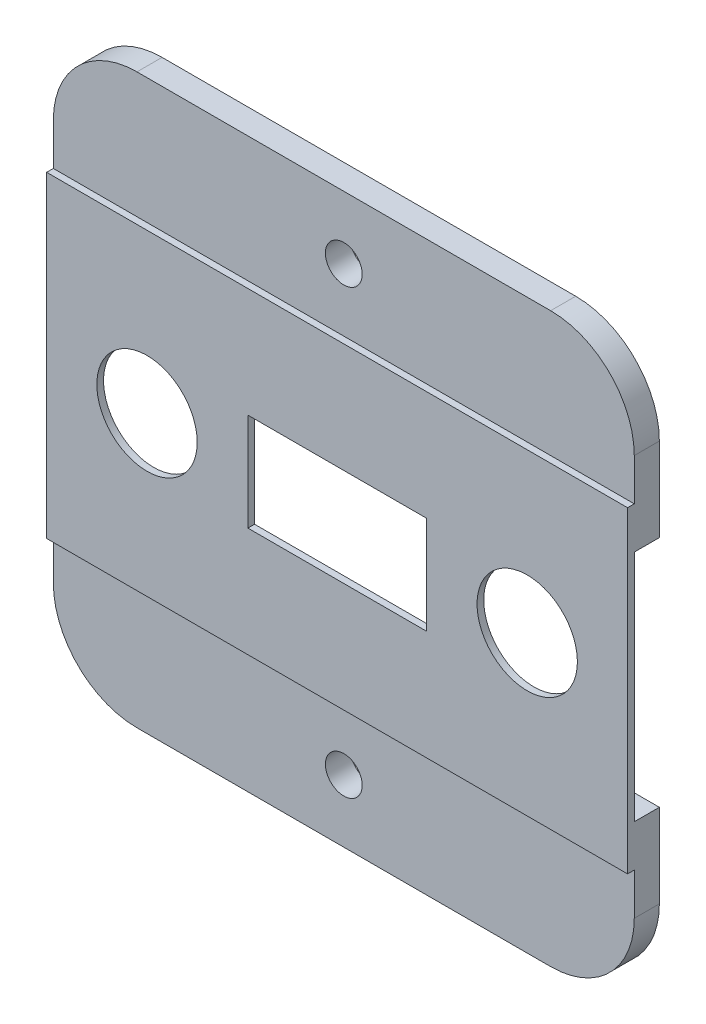
SolidWorks part; units mm, degrees
ref_plane "Front Plane" through (0, 0, 0) normal (0, 0, 1) x (1, 0, 0)
ref_plane "Top Plane" through (0, 0, 0) normal (0, 1, 0) x (1, 0, 0)
ref_plane "Right Plane" through (0, 0, 0) normal (1, 0, 0) x (0, 0, -1)
sketch "Sketch1" plane through (0, 0, 0) normal (0, 0, 1) x (1, 0, 0)
  line L1 (-26.7562, -18.6229) -> (-26.7562, -12.2729)
  line L2 (-20.4062, -5.9229) -> (11.0009, -5.9229)
  line L51 (-14.1451, -18.6229) -> (15.7083, -18.6229)
  line L52 (-26.7562, -18.6229) -> (17.3509, -18.6229) construction
  line L54 (-14.1451, -36.3521) -> (15.7083, -36.3521)
  line L55 (-26.7562, -36.3521) -> (17.3509, -36.3521) construction
  line L56 (-26.7562, -36.3521) -> (17.3509, -36.3521)
  line L57 (-26.7562, -36.3521) -> (-26.7562, -42.7021)
  line L58 (-20.4062, -49.0521) -> (11.0009, -49.0521)
  line L59 (17.3509, -36.3521) -> (17.3509, -42.7021)
  line L60 (17.3509, -18.6229) -> (-26.7562, -18.6229)
  line L61 (17.3509, -18.6229) -> (17.3509, -12.2729)
  circle A0 centre (-19.1362, -27.4875) radius 1.319 construction
  circle A1 centre (9.7309, -27.4875) radius 1.319 construction
  circle A2 centre (-19.1362, -27.4875) radius 1.319 construction
  circle A3 centre (9.7309, -27.4875) radius 1.319 construction
  arc A8 (-20.4062, -49.0521) -> (-26.7562, -42.7021) centre (-20.4062, -42.7021) cw
  arc A9 (11.0009, -49.0521) -> (17.3509, -42.7021) centre (11.0009, -42.7021) ccw
  arc A10 (11.0009, -5.9229) -> (17.3509, -12.2729) centre (11.0009, -12.2729) cw
  arc A11 (-26.7562, -12.2729) -> (-20.4062, -5.9229) centre (-20.4062, -12.2729) cw
  point P0 (17.3509, -8.3311)
  point P3 (-26.7562, -49.0521)
  point P21 (-26.7562, -49.0521)
  dimension "D6" = 7.62
  dimension "D4" = 6.35
  dimension "D3" = 12.7
  dimension "D5" = 7.62
  dimension "D1" = 0.508
  dimension "D2" = 0.508
extrude "Boss-Extrude1" add sketch "Sketch1" along normal offset from surface (1.905 mm away) 0.381 contours L60 L1 A11 L2 A10 L61 | L58 A9 L59 L56 L57 A8
sketch "Sketch2" plane through (0, 0, 1.905) normal (0, 0, 1) x (1, 0, 0)
  line L0 (-10.7161, -30.2624) -> (-10.7161, -30.4402) construction
  line L1 (-26.7562, -39.5271) -> (17.3509, -39.5271)
  line L7 (17.3509, -15.4479) -> (-26.7562, -15.4479)
  line L9 (-10.7161, -30.2624) -> (-10.7161, -24.7125) construction
  line L10 (-10.7161, -24.5347) -> (-10.7161, -24.7125) construction
  line L11 (1.3108, -24.5347) -> (-10.7161, -24.5347) construction
  line L12 (1.3108, -30.4402) -> (1.3108, -24.5347) construction
  line L13 (-10.7161, -30.4402) -> (1.3108, -30.4402) construction
  line L14 (-10.7161, -30.2624) -> (-10.7161, -30.4402) construction
  line L15 (-10.7161, -30.2624) -> (-10.7161, -24.7125) construction
  line L16 (-10.7161, -24.5347) -> (-10.7161, -24.7125) construction
  line L17 (1.3108, -24.5347) -> (-10.7161, -24.5347) construction
  line L18 (1.3108, -30.4402) -> (1.3108, -24.5347) construction
  line L19 (-10.7161, -30.4402) -> (1.3108, -30.4402) construction
  line L20 (-11.4781, -23.7727) -> (-11.4781, -24.7125)
  line L21 (-11.4781, -30.2624) -> (-11.4781, -24.7125)
  line L26 (-11.4781, -30.2624) -> (-11.4781, -31.2022)
  line L27 (-11.4781, -31.2022) -> (2.0728, -31.2022)
  line L30 (2.0728, -31.2022) -> (2.0728, -23.7727)
  line L31 (2.0728, -23.7727) -> (-11.4781, -23.7727)
  line L32 (17.3509, -18.6229) -> (-26.7562, -18.6229) construction
  line L33 (-26.7562, -15.4479) -> (-26.7562, -39.5271)
  line L35 (17.3509, -39.5271) -> (17.3509, -15.4479)
  circle A0 centre (-19.1362, -27.4875) radius 1.397 construction
  circle A1 centre (9.7309, -27.4875) radius 1.397 construction
  circle A2 centre (-19.1362, -27.4875) radius 1.397 construction
  circle A3 centre (9.7309, -27.4875) radius 1.397 construction
  circle A4 centre (9.7309, -27.4875) radius 3.81
  circle A5 centre (-19.1362, -27.4875) radius 3.81
  arc A10 (4.7906, -23.6775) -> (4.7906, -31.2975) centre (4.7906, -27.4875) ccw construction
  point P0 (-25.0322, -39.5329)
  point P37 (-10.7161, -27.4875)
  point P45 (-26.7562, -27.4875)
  dimension "D3" = 0.762
  dimension "D5" = 7.62
  dimension "D1" = 7.62
  dimension "D4" = 3.175
extrude "Boss-Extrude2" add sketch "Sketch2" along normal blind 0.508
sketch "Sketch3" plane through (0, 0, 1.905) normal (0, 0, 1) x (1, 0, 0)
  line L0 (17.3509, -15.4479) -> (-26.7562, -15.4479) construction
  line L1 (-26.7562, -39.5271) -> (17.3509, -39.5271) construction
  line L2 (-20.4062, -49.0521) -> (11.0009, -49.0521) construction
  line L3 (-20.4062, -5.9229) -> (11.0009, -5.9229) construction
  line L4 (17.3509, -15.4479) -> (-26.7562, -15.4479) construction
  line L5 (-26.7562, -39.5271) -> (17.3509, -39.5271) construction
  line L6 (-20.4062, -49.0521) -> (11.0009, -49.0521) construction
  line L7 (-20.4062, -5.9229) -> (11.0009, -5.9229) construction
  line L8 (-4.7027, -5.9229) -> (-4.7027, -15.4479) construction
  line L9 (-4.7027, -39.5271) -> (-4.7027, -49.0521) construction
  point P12 (-4.7027, -44.2896)
  point P13 (-4.7027, -10.6854)
  point P14 (-4.7027, -10.6854)
  point P15 (0, 0)
  point P16 (0, 0)
hole_wizard "#3 Clearance Hole1" positions "Sketch6" profile "Sketch7" hole size "#3" standard "ANSI Inch" end condition through all
sketch "Sketch6" plane through (0, 0, 1.905) normal (0, 0, 1) x (1, 0, 0)
  point P0 (-4.7027, -10.6854)
  point P3 (-4.7027, -44.2896)
sketch "Sketch7" plane through (-4.7027, -10.6854, 1.905) normal (1, 0, 0) x (0, -1, 0)
  line L0 (0, 0) -> (0, 1.905)
  line L1 (0, 1.905) -> (1.397, 1.905)
  line L2 (1.397, 1.905) -> (1.397, 0)
  line L5 (1.397, 0) -> (0, 0)
  line L11 (0, -6.35) -> (0, 107.95) construction
  dimension "Thru Hole Dia." = 2.794
  dimension "Thru Hole Depth" = 1.905
